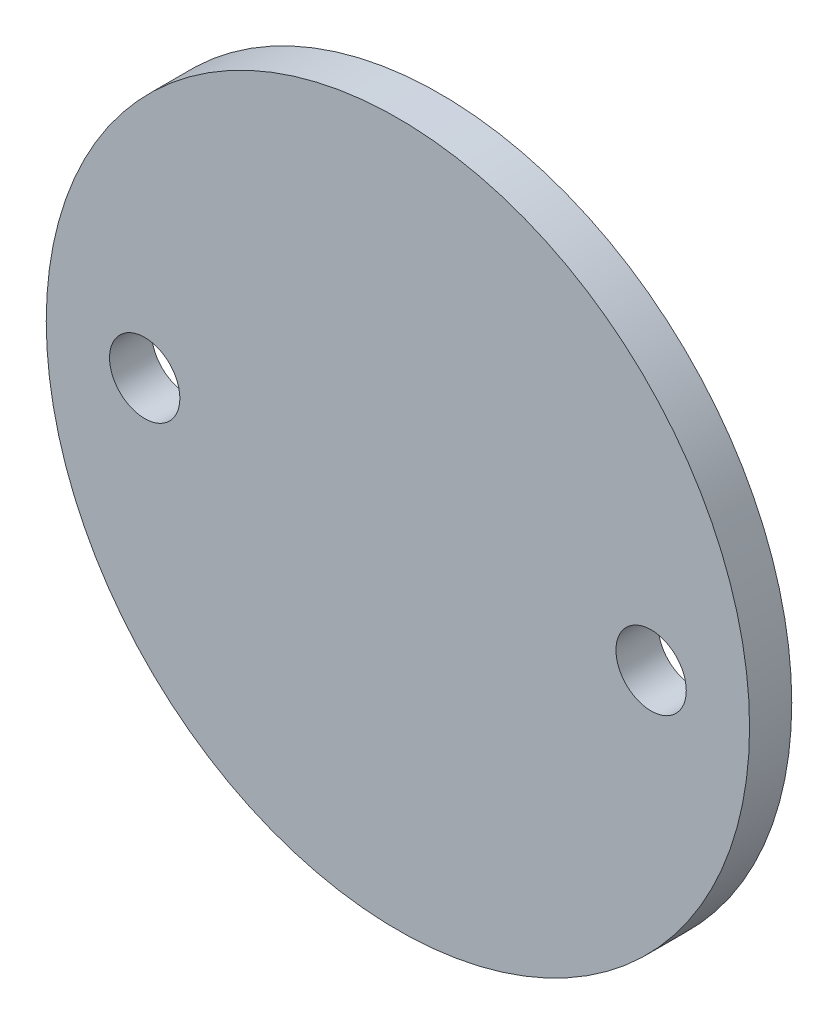
SolidWorks part; units mm, degrees
ref_plane "Front Plane" through (0, 0, 0) normal (0, 0, 1) x (1, 0, 0)
ref_plane "Top Plane" through (0, 0, 0) normal (0, 1, 0) x (1, 0, 0)
ref_plane "Right Plane" through (0, 0, 0) normal (1, 0, 0) x (0, 0, -1)
sketch "Sketch1" plane through (0, 0, 0) normal (0, 0, 1) x (1, 0, 0)
  circle A0 centre (0, 0) radius 25
  circle A1 centre (-18, 0) radius 2.5
  circle A2 centre (18, 0) radius 2.5
  dimension "D1" = 50
  dimension "D2" = 5
  dimension "D3" = 5
  dimension "D4" = 18
  dimension "D5" = 18
extrude "Boss-Extrude1" add sketch "Sketch1" along normal blind 3
